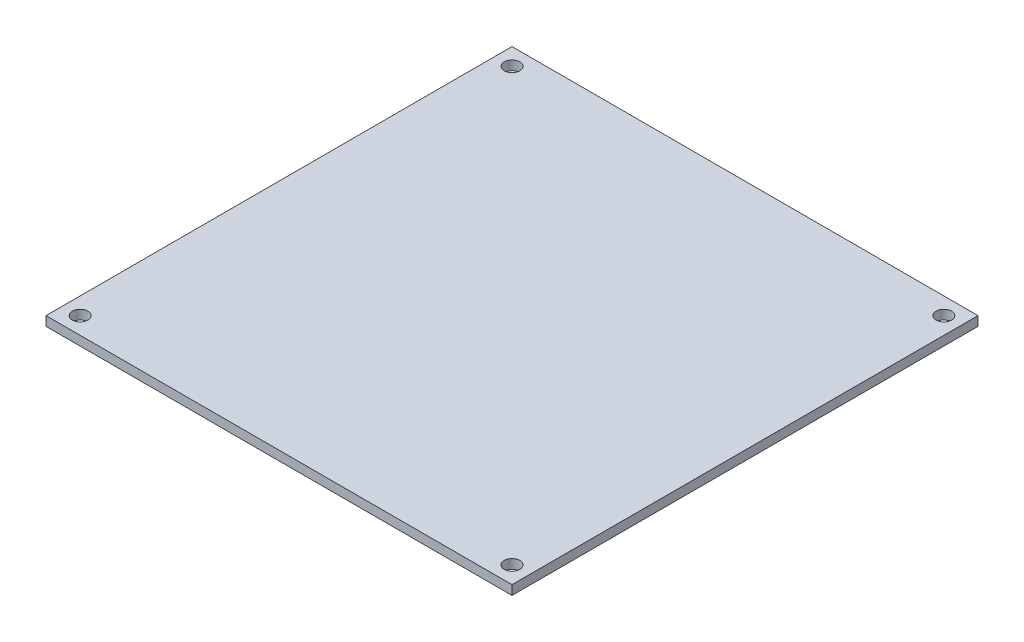
SolidWorks part; units mm, degrees
material "Mogno"
ref_plane "Plano frontal" through (0, 0, 0) normal (0, 0, 1) x (1, 0, 0)
ref_plane "Plano superior" through (0, 0, 0) normal (0, 1, 0) x (1, 0, 0)
ref_plane "Plano direito" through (0, 0, 0) normal (1, 0, 0) x (0, 0, -1)
sketch "Esboço1" plane through (0, 0, 0) normal (0, 1, 0) x (1, 0, 0)
  line L1 (-150, 150) -> (150, 150)
  line L2 (-150, 150) -> (-150, -150)
  line L3 (-150, -150) -> (150, -150)
  line L4 (150, 150) -> (150, -150)
  line L5 (-150, 150) -> (150, -150) construction
  line L6 (-150, -150) -> (150, 150) construction
  point P0 (0, 0)
  dimension "D1" = 300
extrude "Ressalto-extrusão1" add sketch "Esboço1" along normal blind 6
sketch "Esboço2" plane through (0, 6, 0) normal (0, 1, 0) x (1, 0, 0)
  line L0 (-150, 150) -> (-150, -150) construction
  line L1 (-139, 139) -> (139, 139) construction
  line L2 (-139, 139) -> (-139, -139) construction
  line L3 (-139, -139) -> (139, -139) construction
  line L4 (139, 139) -> (139, -139) construction
  line L5 (-139, 139) -> (139, -139) construction
  line L6 (-139, -139) -> (139, 139) construction
  circle A0 centre (-139, 139) radius 5
  circle A1 centre (139, 139) radius 5
  circle A2 centre (139, -139) radius 5
  circle A3 centre (-139, -139) radius 5
  point P0 (0, 0)
  dimension "D2" = 10
  dimension "D1" = 11
extrude "Corte-extrusão1" cut sketch "Esboço2" against normal through all
